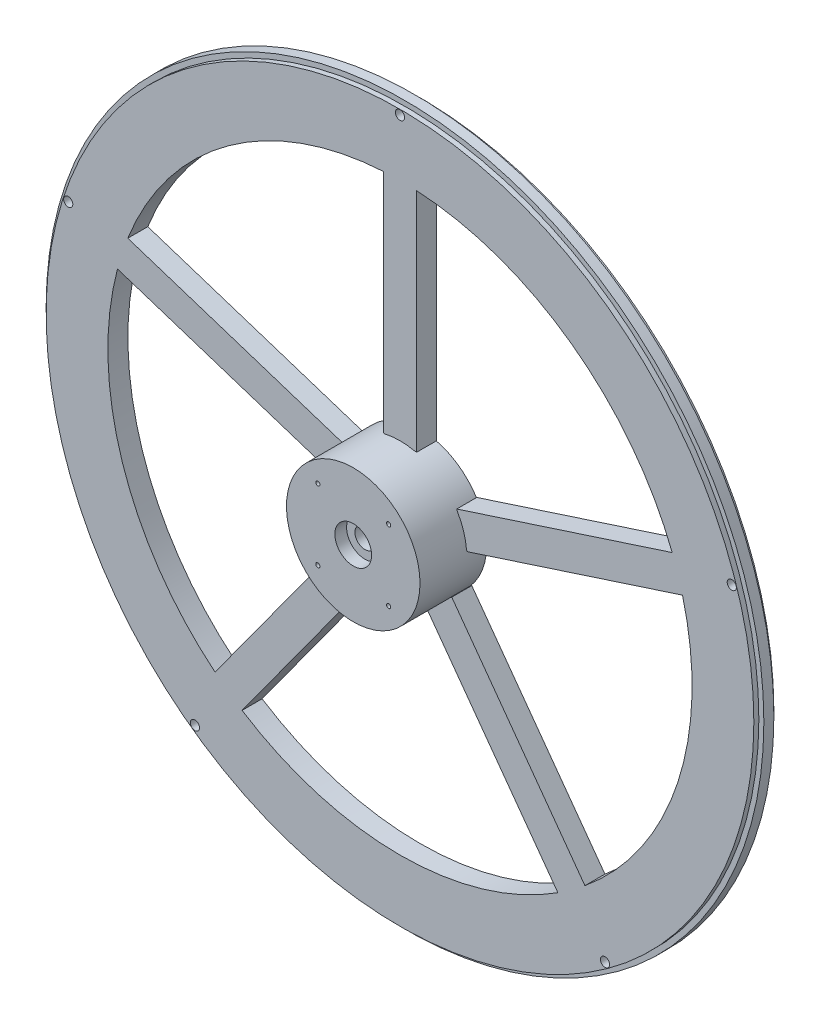
SolidWorks part; units mm, degrees
ref_plane "Front Plane" through (0, 0, 0) normal (0, 0, 1) x (1, 0, 0)
ref_plane "Top Plane" through (0, 0, 0) normal (0, 1, 0) x (1, 0, 0)
ref_plane "Right Plane" through (0, 0, 0) normal (1, 0, 0) x (0, 0, -1)
sketch "Sketch1" plane through (0, 0, 0) normal (0, 0, 1) x (1, 0, 0)
  circle A0 centre (0, 0) radius 215
  circle A1 centre (0, 0) radius 175
extrude "Ring" add sketch "Sketch1" along normal blind 12
sketch "Sketch2" plane through (0, 0, 0) normal (0, 0, 1) x (1, 0, 0)
  circle A0 centre (0, 0) radius 40
extrude "Hub" add sketch "Sketch2" along normal blind 40
sketch "Sketch3" plane through (0, 0, 0) normal (0, 0, 1) x (1, 0, 0)
  line L0 (40.1814, 2.5411) -> (170.4761, 44.8764)
  line L1 (170.4761, 44.8764) -> (164.2958, 63.8976)
  line L2 (164.2958, 63.8976) -> (34.001, 21.5622)
  line L3 (34.001, 21.5622) -> (40.1814, 2.5411)
  line L4 (10, 39) -> (10, 176)
  line L5 (10, 176) -> (-10, 176)
  line L6 (-10, 176) -> (-10, 39)
  line L7 (-10, 39) -> (10, 39)
  line L8 (-34.001, 21.5622) -> (-164.2958, 63.8976)
  line L9 (-164.2958, 63.8976) -> (-170.4761, 44.8764)
  line L10 (-170.4761, 44.8764) -> (-40.1814, 2.5411)
  line L11 (-40.1814, 2.5411) -> (-34.001, 21.5622)
  line L12 (-31.0138, -25.6738) -> (-111.5404, -136.5091)
  line L13 (-111.5404, -136.5091) -> (-95.36, -148.2648)
  line L14 (-95.36, -148.2648) -> (-14.8335, -37.4295)
  line L15 (-14.8335, -37.4295) -> (-31.0138, -25.6738)
  line L16 (14.8335, -37.4295) -> (95.36, -148.2648)
  line L17 (95.36, -148.2648) -> (111.5404, -136.5091)
  line L18 (111.5404, -136.5091) -> (31.0138, -25.6738)
  line L19 (31.0138, -25.6738) -> (14.8335, -37.4295)
extrude "Spokes" add sketch "Sketch3" along normal blind 12
sketch "Sketch4" plane through (0, 0, 0) normal (0, 0, 1) x (1, 0, 0)
  circle A0 centre (0, 0) radius 6
extrude "Bore" cut sketch "Sketch4" along normal blind 40
sketch "Sketch5" plane through (0, 0, 0) normal (0, 0, 1) x (1, 0, 0)
  circle A0 centre (0, 0) radius 11
extrude "Bearing_seat_low" cut sketch "Sketch5" along normal blind 7
ref_plane "Plane_z33" through (0, 0, 33) normal (0, 0, 1) x (1, 0, 0)
sketch "Sketch6" plane through (0, 0, 33) normal (0, 0, 1) x (1, 0, 0)
  circle A0 centre (0, 0) radius 11
extrude "Bearing_seat_high" cut sketch "Sketch6" along normal blind 7
sketch "Sketch7" plane through (0, 0, 0) normal (0, 0, 1) x (1, 0, 0)
  circle A0 centre (0, 0) radius 216
  circle A1 centre (0, 0) radius 212
extrude "Band_rabbet" cut sketch "Sketch7" along normal blind 3
ref_plane "Plane_z9" through (0, 0, 9) normal (0, 0, 1) x (1, 0, 0)
sketch "Sketch8" plane through (0, 0, 9) normal (0, 0, 1) x (1, 0, 0)
  circle A0 centre (0, 0) radius 216
  circle A1 centre (0, 0) radius 212
extrude "Cover_rabbet" cut sketch "Sketch8" along normal blind 3
sketch "Sketch9" plane through (0, 0, 0) normal (0, 0, 1) x (1, 0, 0)
  circle A0 centre (198.7708, 64.5846) radius 2.75
  circle A1 centre (0, 209) radius 2.75
  circle A2 centre (-198.7708, 64.5846) radius 2.75
  circle A3 centre (-122.8471, -169.0846) radius 2.75
  circle A4 centre (122.8471, -169.0846) radius 2.75
extrude "Rod_holes" cut sketch "Sketch9" along normal blind 12
ref_plane "Plane_z32" through (0, 0, 32) normal (0, 0, 1) x (1, 0, 0)
sketch "Sketch10" plane through (0, 0, 32) normal (0, 0, 1) x (1, 0, 0)
  circle A0 centre (21.2132, 21.2132) radius 1.25
  circle A1 centre (-21.2132, 21.2132) radius 1.25
  circle A2 centre (-21.2132, -21.2132) radius 1.25
  circle A3 centre (21.2132, -21.2132) radius 1.25
extrude "Grommet_screws" cut sketch "Sketch10" along normal blind 8
